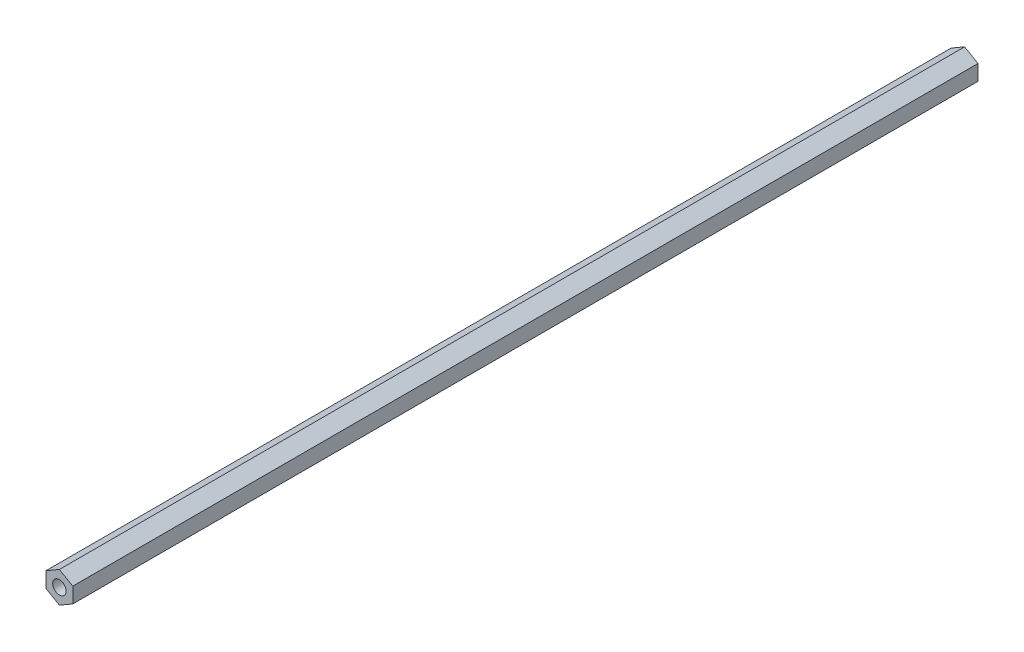
SolidWorks part; units mm, degrees
material "6061 Alloy"
ref_plane "Front Plane" through (0, 0, 0) normal (0, 0, 1) x (1, 0, 0)
ref_plane "Top Plane" through (0, 0, 0) normal (0, 1, 0) x (1, 0, 0)
ref_plane "Right Plane" through (0, 0, 0) normal (1, 0, 0) x (0, 0, -1)
sketch "Sketch1" plane through (0, 0, 0) normal (0, 0, 1) x (1, 0, 0)
  line L1 (0, 7.3323) -> (-6.35, 3.6662) construction
  line L2 (-6.35, 3.6662) -> (-6.35, -3.6662) construction
  line L3 (-6.35, -3.6662) -> (0, -7.3323) construction
  line L4 (0, -7.3323) -> (6.35, -3.6662) construction
  line L5 (6.35, -3.6662) -> (6.35, 3.6662) construction
  line L6 (6.35, 3.6662) -> (0, 7.3323) construction
  circle A2 centre (0, 0) radius 6.35 construction
  dimension "Width" = 12.7
sketch "Sketch2" plane through (0, 0, 0) normal (1, 0, 0) x (0, 0, -1)
  line L0 (-214.63, 7.3323) -> (214.63, 7.3323) construction
  point P2 (0, 7.3323)
  point P3 (182.88, 7.3323)
  point P4 (-182.88, 7.3323)
  dimension "Length" = 429.26
  dimension "D2" = 31.75
  dimension "D1" = 31.75
sketch "Sketch3" plane through (0, 0, 0) normal (0, 0, 1) x (1, 0, 0)
  line L0 (-6.35, -3.6662) -> (0, -7.3323) construction
  line L1 (0, -7.3323) -> (6.35, -3.6662) construction
  line L2 (6.35, -3.6662) -> (6.35, 3.6662) construction
  line L3 (6.35, 3.6662) -> (0, 7.3323) construction
  line L4 (0, 7.3323) -> (-6.35, 3.6662) construction
  line L5 (-6.35, 3.6662) -> (-6.35, -3.6662) construction
  line L6 (-6.35, -3.6662) -> (0, -7.3323)
  line L7 (0, -7.3323) -> (6.35, -3.6662)
  line L8 (6.35, -3.6662) -> (6.35, 3.6662)
  line L9 (6.35, 3.6662) -> (0, 7.3323)
  line L10 (0, 7.3323) -> (-6.35, 3.6662)
  line L11 (-6.35, 3.6662) -> (-6.35, -3.6662)
extrude "Boss-Extrude2" add sketch "Sketch3" along normal up to vertex (214.63 mm away) and the other way up to vertex (214.63 mm away) up to point (0, 7.3323, 214.63) other way up to point (0, 7.3323, -214.63)
sketch "Sketch4" plane through (0, 0, 214.63) normal (0, 0, 1) x (1, 0, 0)
  point P0 (0, 0)
hole_wizard "1/4 (0.25) Diameter Hole1" positions "Sketch5" profile "Sketch6" hole size "1/4" standard "ANSI Inch"
sketch "Sketch5" plane through (0, 0, 214.63) normal (0, 0, 1) x (1, 0, 0)
  point P0 (0, 0)
sketch "Sketch6" plane through (0, 0, 214.63) normal (1, 0, 0) x (0, -1, 0)
  line L0 (0, 0) -> (0, 27.3077)
  line L1 (0, 27.3077) -> (3.175, 25.4)
  line L2 (3.175, 25.4) -> (3.175, 0)
  line L5 (3.175, 0) -> (0, 0)
  line L10 (0, 27.3077) -> (-3.175, 25.4) construction
  line L11 (0, -6.35) -> (0, 107.95) construction
  dimension "Hole Dia." = 6.35
  dimension "Hole Depth" = 25.4
  dimension "Drill Angle" = 118
hole_wizard "1/4 (0.25) Diameter Hole2" positions "Sketch7" profile "Sketch8" hole size "1/4" standard "ANSI Inch"
sketch "Sketch7" plane through (0, 0, -214.63) normal (0, 0, -1) x (-1, 0, 0)
  point P0 (0, 0)
sketch "Sketch8" plane through (0, 0, -214.63) normal (1, 0, 0) x (0, 1, 0)
  line L0 (0, 0) -> (0, 27.3077)
  line L1 (0, 27.3077) -> (3.175, 25.4)
  line L2 (3.175, 25.4) -> (3.175, 0)
  line L5 (3.175, 0) -> (0, 0)
  line L10 (0, 27.3077) -> (-3.175, 25.4) construction
  line L11 (0, -6.35) -> (0, 107.95) construction
  dimension "Hole Dia." = 6.35
  dimension "Hole Depth" = 25.4
  dimension "Drill Angle" = 118
equation "\"D2@Sketch2\" = \"D1@Sketch2\""
equation "\"D1@Sketch2\" = \"Width@Sketch1\" * 2.5"
